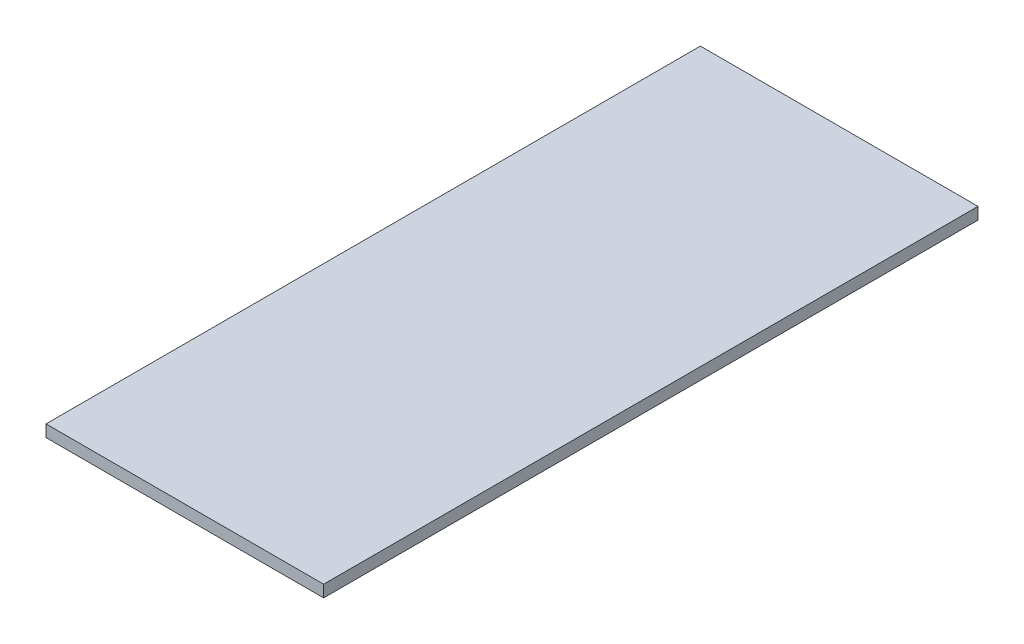
SolidWorks part; units mm, degrees
material "Silicon"
ref_plane "Front Plane" through (0, 0, 0) normal (0, 0, 1) x (1, 0, 0)
ref_plane "Top Plane" through (0, 0, 0) normal (0, 1, 0) x (1, 0, 0)
ref_plane "Right Plane" through (0, 0, 0) normal (1, 0, 0) x (0, 0, -1)
sketch "Sketch1" plane through (0, 0, 0) normal (0, 1, 0) x (1, 0, 0)
  line L1 (-3.5, -8.25) -> (3.5, -8.25)
  line L2 (-3.5, -8.25) -> (-3.5, 8.25)
  line L3 (-3.5, 8.25) -> (3.5, 8.25)
  line L4 (3.5, -8.25) -> (3.5, 8.25)
  line L5 (-3.5, -8.25) -> (3.5, 8.25) construction
  line L6 (-3.5, 8.25) -> (3.5, -8.25) construction
  point P0 (0, 0)
  dimension "D1" = 7
  dimension "D2" = 16.5
extrude "Boss-Extrude1" add sketch "Sketch1" along normal mid plane 0.3
